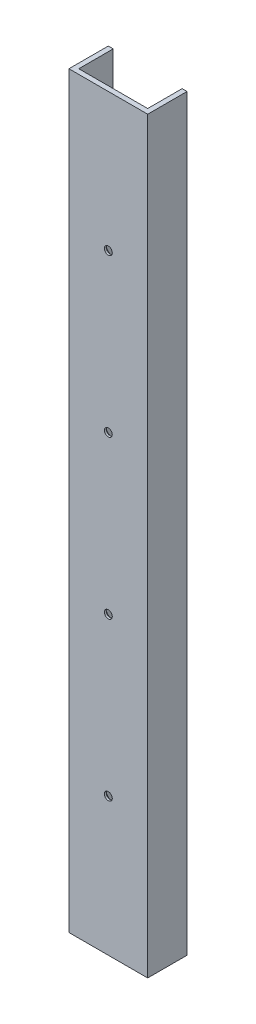
SolidWorks part; units mm, degrees
material "6061 Alloy"
ref_plane "Front Plane" through (0, 0, 0) normal (0, 0, 1) x (1, 0, 0)
ref_plane "Top Plane" through (0, 0, 0) normal (0, 1, 0) x (1, 0, 0)
ref_plane "Right Plane" through (0, 0, 0) normal (1, 0, 0) x (0, 0, -1)
sketch "Sketch1" plane through (0, 0, 0) normal (0, 1, 0) x (1, 0, 0)
  line L0 (-25.4, 12.7) -> (-25.4, -12.7)
  line L1 (-25.4, -12.7) -> (25.4, -12.7)
  line L2 (25.4, -12.7) -> (25.4, 12.7)
  line L3 (25.4, 12.7) -> (22.225, 12.7)
  line L4 (22.225, 12.7) -> (22.225, -9.525)
  line L5 (22.225, -9.525) -> (-22.225, -9.525)
  line L6 (-22.225, -9.525) -> (-22.225, 12.7)
  line L7 (-22.225, 12.7) -> (-25.4, 12.7)
  line L8 (0, -9.525) -> (0, -12.7) construction
  point P2 (0, -9.525)
  point P9 (-25.4, 0)
  dimension "D1" = 25.4
  dimension "D2" = 50.8
  dimension "D3" = 3.175
extrude "Boss-Extrude1" add sketch "Sketch1" along normal mid plane 482.6
hole_wizard "CSK for #10 Flat Head Machine Screw (100)1" positions "3DSketch1" profile "Sketch2" countersink size "#10" standard "ANSI Inch" end condition through all
sketch3d "3DSketch1"
  line L0 (0, -241.3, 9.525) -> (0, 241.3, 9.525)
  line L1 (22.225, -241.3, 9.525) -> (-22.225, -241.3, 9.525) construction
  line L2 (22.225, 241.3, 9.525) -> (-22.225, 241.3, 9.525) construction
  point P10 (0, -152.4, 9.525)
  dimension "D1" = 88.9
sketch "Sketch2" plane through (0, -152.4, 9.525) normal (1, 0, 0) x (0, 1, 0)
  line L0 (0, 0) -> (0, 3.175)
  line L1 (0, 3.175) -> (2.5527, 3.175)
  line L2 (2.5527, 3.175) -> (2.5527, 1.9608)
  line L3 (2.5527, 1.9608) -> (4.8895, 0)
  line L5 (4.8895, 0) -> (0, 0)
  line L6 (-2.5527, 1.9608) -> (-4.8895, 0) construction
  line L11 (0, -6.35) -> (0, 107.95) construction
  dimension "Thru Hole Dia." = 5.1054
  dimension "Thru Hole Depth" = 3.175
  dimension "Near C'Sink Dia." = 9.779
  dimension "Near C'Sink Angle" = 100
pattern_linear "LPattern1" count 4 spacing 101.6 along (0, 1, 0) of "CSK for #10 Flat Head Machine Screw (100)1"
